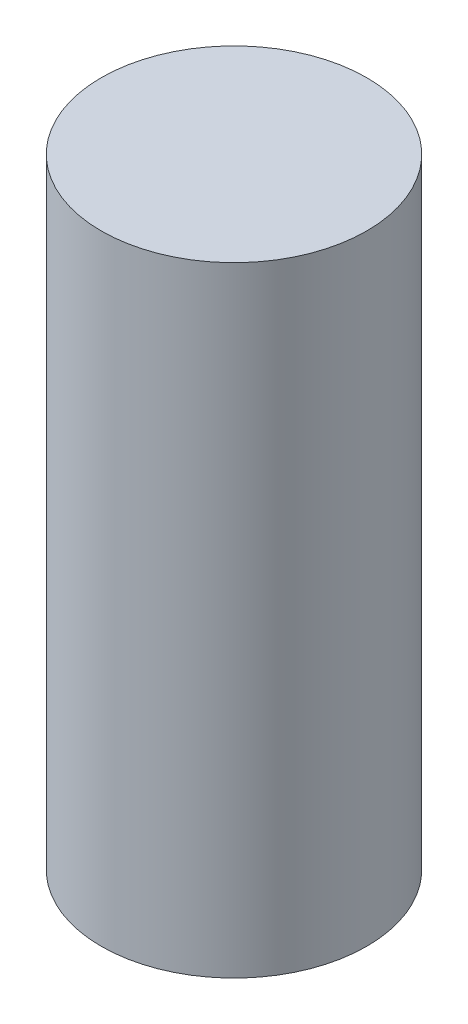
SolidWorks part; units mm, degrees
ref_plane "Front Plane" through (0, 0, 0) normal (0, 0, 1) x (1, 0, 0)
ref_plane "Top Plane" through (0, 0, 0) normal (0, 1, 0) x (1, 0, 0)
ref_plane "Right Plane" through (0, 0, 0) normal (1, 0, 0) x (0, 0, -1)
other "Configuration Table"
sketch "Sketch1" plane through (0, 0, 0) normal (0, 1, 0) x (1, 0, 0)
  circle A0 centre (50, 770) radius 6
extrude "OVEN_ayar_mil_3" add sketch "Sketch1" along normal blind 28 from offset 12 separate body
